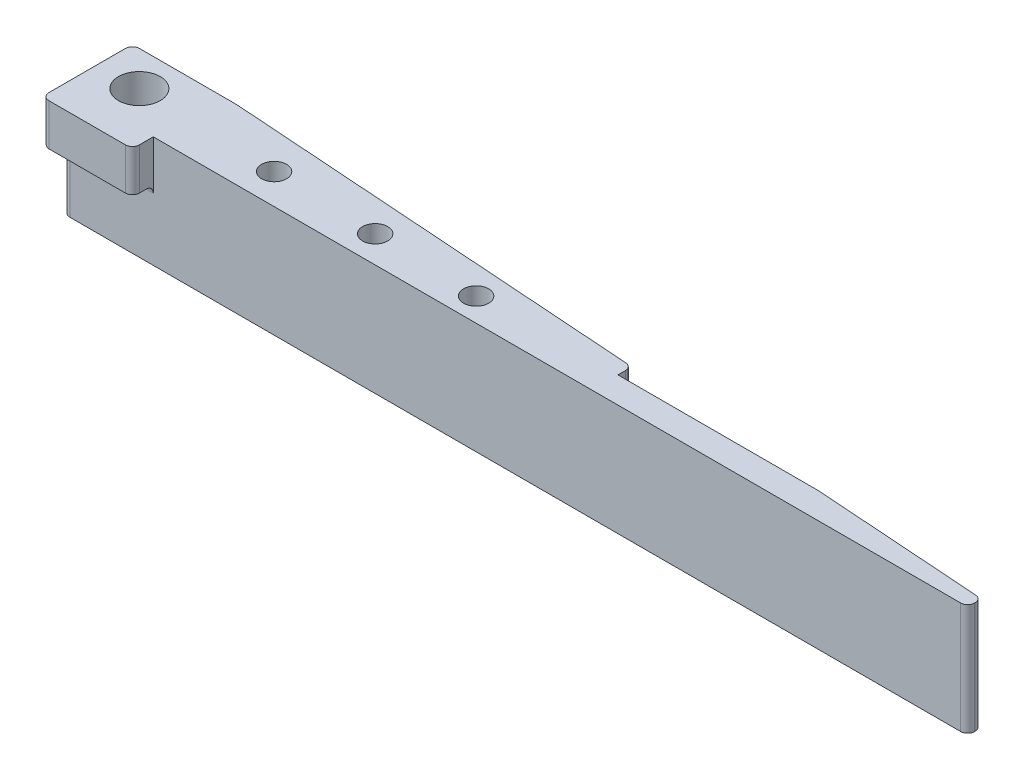
SolidWorks part; units mm, degrees
ref_plane "Front Plane" through (0, 0, 0) normal (0, 0, 1) x (1, 0, 0)
ref_plane "Top Plane" through (0, 0, 0) normal (0, 1, 0) x (1, 0, 0)
ref_plane "Right Plane" through (0, 0, 0) normal (1, 0, 0) x (0, 0, -1)
sketch "Sketch1" plane through (0, 0, 0) normal (0, 1, 0) x (1, 0, 0)
  line L0 (157.48, -3.81) -> (11.43, 6.35)
  line L1 (-7.62, 6.35) -> (11.43, 6.35)
  line L2 (-7.62, 6.35) -> (-7.62, -6.35)
  line L3 (-7.62, -6.35) -> (157.48, -6.35)
  line L4 (157.48, -3.81) -> (157.48, -6.35)
  line L5 (0, 0) -> (157.48, -5.08) construction
  circle A0 centre (0, 0) radius 3.81
  circle A1 centre (25.4, -0.8194) radius 2.286
  circle A3 centre (44.45, -1.4339) radius 2.286
  circle A4 centre (63.5, -2.0484) radius 2.286
  point P7 (-7.62, 0)
  dimension "D3" = 7.62
  dimension "D7" = 4.572
  dimension "D1" = 12.7
  dimension "D2" = 7.62
  dimension "D4" = 165.1
  dimension "D5" = 19.05
  dimension "D6" = 2.54
  dimension "D9" = 25.4
  dimension "D10" = 38.1
  dimension "D8" = 3
extrude "Boss-Extrude1" add sketch "Sketch1" along normal blind 7.62
sketch "Sketch2" plane through (0, 0, 0) normal (0, -1, 0) x (-1, 0, 0)
  line L0 (-157.48, -6.35) -> (-157.48, -3.81)
  line L1 (-27.3064, -4.1214) -> (-23.4936, -4.1214)
  line L2 (-23.4936, -4.1214) -> (-21.5872, -0.8194)
  line L3 (-21.5872, -0.8194) -> (-23.4936, 2.4826)
  line L4 (-23.4936, 2.4826) -> (-27.3064, 2.4826)
  line L5 (-27.3064, 2.4826) -> (-29.2128, -0.8194)
  line L6 (-29.2128, -0.8194) -> (-27.3064, -4.1214)
  line L7 (-40.6372, -1.4339) -> (-42.5436, 1.8681)
  line L8 (-42.5436, 1.8681) -> (-46.3564, 1.8681)
  line L9 (-46.3564, 1.8681) -> (-48.2628, -1.4339)
  line L10 (-48.2628, -1.4339) -> (-46.3564, -4.7359)
  line L11 (-46.3564, -4.7359) -> (-42.5436, -4.7359)
  line L12 (-42.5436, -4.7359) -> (-40.6372, -1.4339)
  line L13 (-59.6872, -2.0484) -> (-61.5936, 1.2536)
  line L14 (-61.5936, 1.2536) -> (-65.4064, 1.2536)
  line L15 (-65.4064, 1.2536) -> (-67.3128, -2.0484)
  line L16 (-67.3128, -2.0484) -> (-65.4064, -5.3504)
  line L17 (-65.4064, -5.3504) -> (-61.5936, -5.3504)
  line L18 (-61.5936, -5.3504) -> (-59.6872, -2.0484)
  line L19 (-157.48, -3.81) -> (-11.43, 6.35)
  line L21 (7.62, 6.35) -> (7.62, -6.35) construction
  line L22 (7.62, -6.35) -> (-157.48, -6.35)
  line L23 (-11.43, 6.35) -> (7.62, 6.35)
  line L24 (7.62, 6.35) -> (-11.43, 6.35) construction
  line L25 (7.62, 6.35) -> (7.62, -6.35)
  line L26 (7.62, -6.35) -> (-157.48, -6.35) construction
  circle A0 centre (-25.4, -0.8194) radius 3.302 construction
  circle A1 centre (-44.45, -1.4339) radius 3.302 construction
  circle A2 centre (-63.5, -2.0484) radius 3.302 construction
  circle A3 centre (0, 0) radius 3.81
  dimension "D1" = 6.604
extrude "Boss-Extrude2" add sketch "Sketch2" along normal blind 12.7
sketch "Sketch4" plane through (0, 7.62, 0) normal (0, 1, 0) x (1, 0, 0)
  line L0 (88.9, 0.9608) -> (88.9, -1.5792)
  line L1 (157.48, -3.81) -> (11.43, 6.35) construction
  line L2 (88.9, -1.5792) -> (125.4125, -1.5792)
  line L3 (88.9, 0.9608) -> (125.4125, -1.5792)
  dimension "D1" = 2.54
  dimension "D2" = 88.9
extrude "Cut-Extrude1" cut sketch "Sketch4" against normal through all
sketch "Sketch5" plane through (0, 0, 0) normal (0, -1, 0) x (1, 0, 0)
  line L0 (-7.62, 6.35) -> (-7.62, -6.35) construction
  line L1 (8.89, 6.35) -> (-7.62, 6.35)
  line L2 (8.89, 6.35) -> (8.89, 10.16)
  line L3 (8.89, 10.16) -> (-7.62, 10.16)
  line L4 (-7.62, 6.35) -> (-7.62, 10.16)
  line L5 (157.48, 6.35) -> (-7.62, 6.35) construction
  dimension "D1" = 3.81
  dimension "D2" = 16.51
extrude "Boss-Extrude3" add sketch "Sketch5" against normal up to surface (7.62 mm away) up to face at (76.7953, 7.62, 0.751)
sketch "Sketch6" plane through (0, 7.62, 0) normal (0, 1, 0) x (1, 0, 0)
  line L0 (-7.62, -10.16) -> (-31.75, -10.16)
  line L1 (-31.75, -10.16) -> (-31.75, 2.54)
  line L2 (-31.75, 2.54) -> (-7.62, 6.35)
  line L4 (-7.62, 6.35) -> (-7.62, -10.16)
  line L5 (-7.62, 6.35) -> (11.43, 6.35) construction
  circle A0 centre (-25.4, -3.81) radius 1.778
  dimension "D6" = 3.556
  dimension "D1" = 12.7
  dimension "D2" = 6.35
  dimension "D3" = 6.35
  dimension "D4" = 25.4
  dimension "D5" = 3.81
extrude "Boss-Extrude4" [suppressed] add sketch "Sketch6" against normal up to surface (7.62 mm away)
fillet "Fillet1" [suppressed] radius 6.35
fillet "Fillet2" radius 1.27 5 edges at (88.9, -2.54, -0.9608) (0.635, 0, 6.35) (8.89, 3.81, 10.16) (157.48, -2.54, 3.81) (157.48, -2.54, 6.35)
fillet "Fillet3" radius 1.27 1 edges at (-7.62, -2.54, -6.35)
fillet "Fillet4" radius 1.27 4 edges at (-7.62, 0, 8.89) (-7.62, -0.372, 6.722) (-7.62, -6.985, 6.35) (-7.62, 3.81, 10.16)
